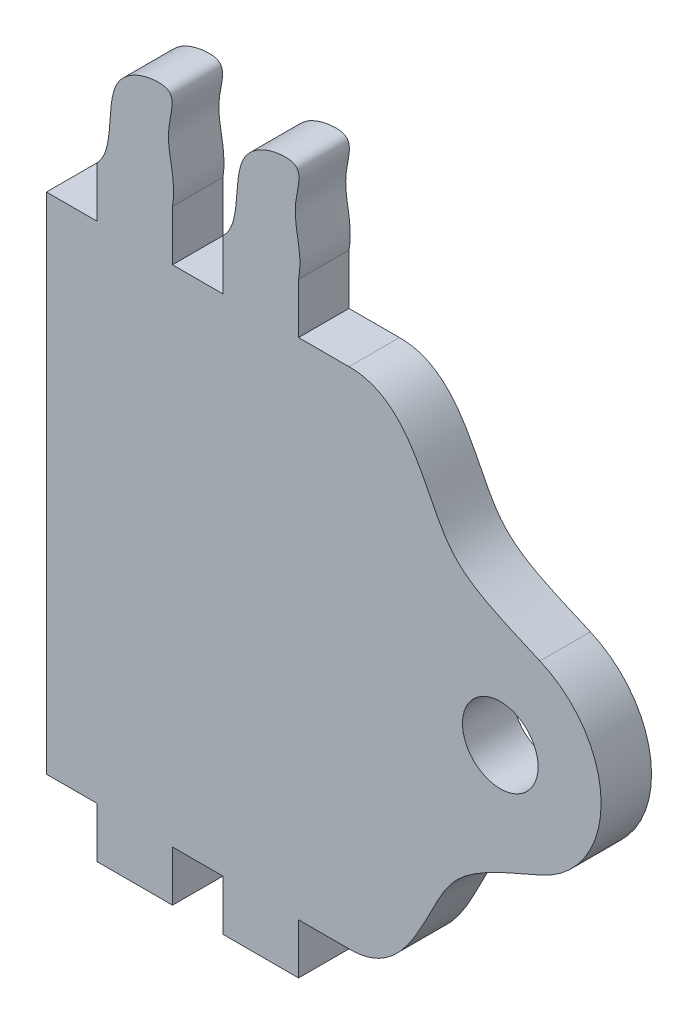
SolidWorks part; units mm, degrees
ref_plane "Front Plane" through (0, 0, 0) normal (0, 0, 1) x (1, 0, 0)
ref_plane "Top Plane" through (0, 0, 0) normal (0, 1, 0) x (1, 0, 0)
ref_plane "Right Plane" through (0, 0, 0) normal (1, 0, 0) x (0, 0, -1)
sketch "Sketch1" plane through (0, 0, 0) normal (0, 0, 1) x (1, 0, 0)
  line L0 (0, 0) -> (-3.2347, 0)
  line L1 (9.525, -15.875) -> (-9.525, -15.875)
  line L2 (9.525, -15.875) -> (9.525, 15.875)
  line L3 (9.525, 15.875) -> (-9.525, 15.875)
  line L4 (-9.525, -15.875) -> (-9.525, 15.875)
  line L5 (9.525, -15.875) -> (-9.525, 15.875) construction
  line L6 (9.525, 15.875) -> (-9.525, -15.875) construction
  line L7 (6.35, -15.875) -> (6.35, -19.05)
  line L8 (-6.35, 15.875) -> (-1.5875, 15.875)
  line L9 (-6.35, 15.875) -> (-6.35, 19.05)
  line L10 (-6.35, 19.05) -> (-1.5875, 19.05)
  line L11 (-1.5875, 15.875) -> (-1.5875, 19.05)
  line L12 (1.5875, 15.875) -> (6.35, 15.875)
  line L13 (1.5875, 15.875) -> (1.5875, 19.05)
  line L14 (1.5875, 19.05) -> (6.35, 19.05)
  line L15 (6.35, 15.875) -> (6.35, 19.05)
  line L16 (1.5875, -15.875) -> (1.5875, -19.05)
  line L17 (1.5875, -19.05) -> (6.35, -19.05)
  line L18 (-6.35, -15.875) -> (-6.35, -19.05)
  line L19 (-6.35, -19.05) -> (-1.5875, -19.05)
  line L20 (-1.5875, -15.875) -> (-1.5875, -19.05)
  line L21 (0, 0) -> (0, 5.2608)
  circle A2 centre (19.05, 0) radius 2.3813
  circle A3 centre (19.05, 0) radius 6.35
  spline S1 degree 3 poles (-6.35, 19.05) (-5.1089, 20.3128) (-6.2488, 23.7826) (-3.5047, 25.4227) (-1.2706, 25.4019) (-2.3305, 22.1182) (-1.303, 20.9023) (-1.5875, 19.05) knots 0 0 0 0 0.348301 0.511854 0.587996 0.709542 1 1 1 1
  spline S2 degree 3 poles (1.5875, 19.05) (2.8761, 20.283) (1.7509, 23.717) (4.4801, 25.3439) (6.714, 25.3233) (5.6646, 22.0756) (6.6616, 20.8588) (6.35, 19.05) knots 0 0 0 0 0.347504 0.512636 0.589513 0.712232 1 1 1 1
  spline S4 degree 3 poles (21.5476, -5.8382) (17.7414, -7.4665) (15.0309, -8.8365) (13.0093, -15.9171) (9.525, -15.875) knots 0 0 0 0 0.458191 1 1 1 1
  spline S5 degree 3 poles (21.5476, 5.8382) (17.7414, 7.4665) (15.0309, 8.8365) (13.0093, 15.9171) (9.525, 15.875) knots 0 0 0 0 0.458191 1 1 1 1
  point P0 (0, 0)
  dimension "D1" = 19.05
  dimension "D2" = 31.75
  dimension "D6" = 4.7625
  dimension "D7" = 4.7625
  dimension "D8" = 3.175
  dimension "D9" = 3.175
  dimension "D10" = 3.175
  dimension "D11" = 3.175
extrude "Boss-Extrude1" add sketch "Sketch1" along normal blind 3.175
